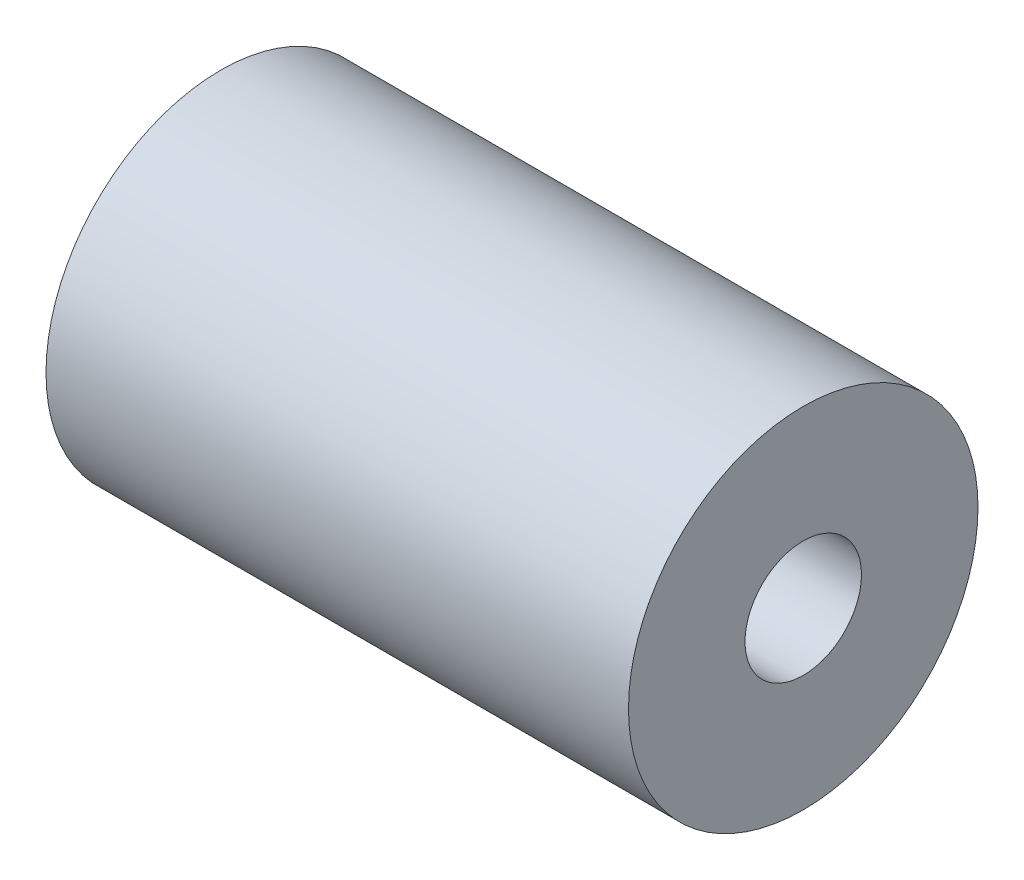
SolidWorks part; units mm, degrees
ref_plane "前视基准面" through (0, 0, 0) normal (0, 0, 1) x (1, 0, 0)
ref_plane "上视基准面" through (0, 0, 0) normal (0, 1, 0) x (1, 0, 0)
ref_plane "右视基准面" through (0, 0, 0) normal (1, 0, 0) x (0, 0, -1)
other "Configuration Table"
sketch "草图1" plane through (0, 0, 0) normal (1, 0, 0) x (0, 0, -1)
  circle A0 centre (0, 0) radius 3
  circle A1 centre (0, 0) radius 1
  dimension "D1" = 6
  dimension "D2" = 2
extrude "凸台-拉伸1" add sketch "草图1" along normal blind 10 contours A0 | A1
sketch "草图3" plane through (0, 0, 0) normal (0, 0, 1) x (1, 0, 0)
  line L0 (5, 3) -> (5, -3)
  line L1 (10, 3) -> (0, 3) construction
  line L2 (0, -3) -> (10, -3) construction
  line L3 (5, 0) -> (8.8849, 0)
  point P9 (0, 0)
